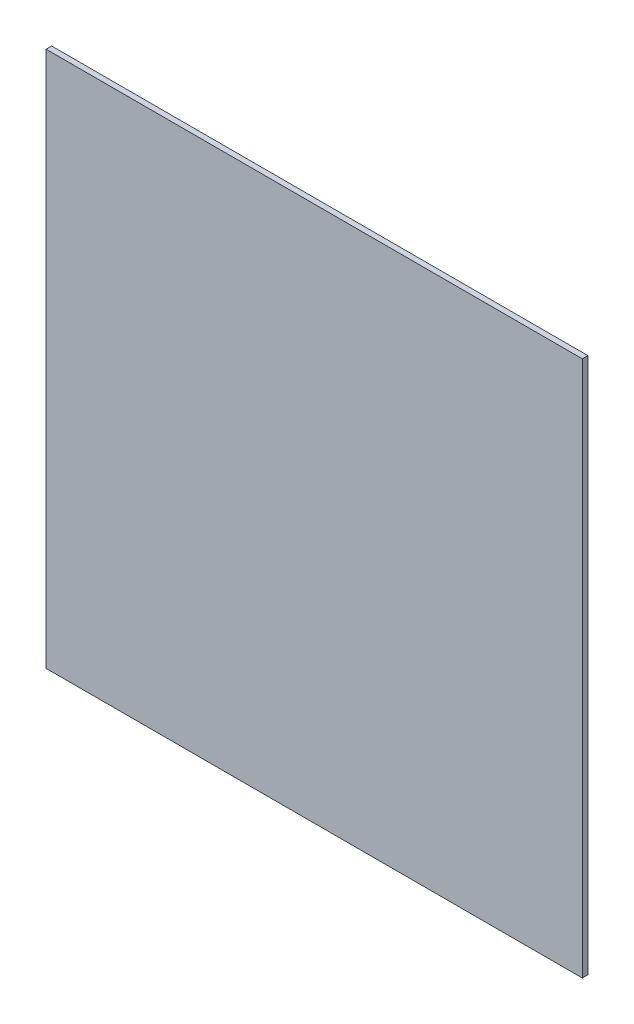
SolidWorks part; units mm, degrees
ref_plane "Front" through (0, 0, 0) normal (0, 0, 1) x (1, 0, 0)
ref_plane "Top" through (0, 0, 0) normal (0, 1, 0) x (1, 0, 0)
ref_plane "Right" through (0, 0, 0) normal (1, 0, 0) x (0, 0, -1)
sketch "Sketch1" plane through (0, 0, 0) normal (0, 0, 1) x (1, 0, 0)
  line L1 (0, 0) -> (304.8, 0)
  line L2 (0, 0) -> (0, 304.8)
  line L3 (0, 304.8) -> (304.8, 304.8)
  line L4 (304.8, 0) -> (304.8, 304.8)
  dimension "D1" = 304.8
extrude "Boss-Extrude1" add sketch "Sketch1" along normal blind 3.175
